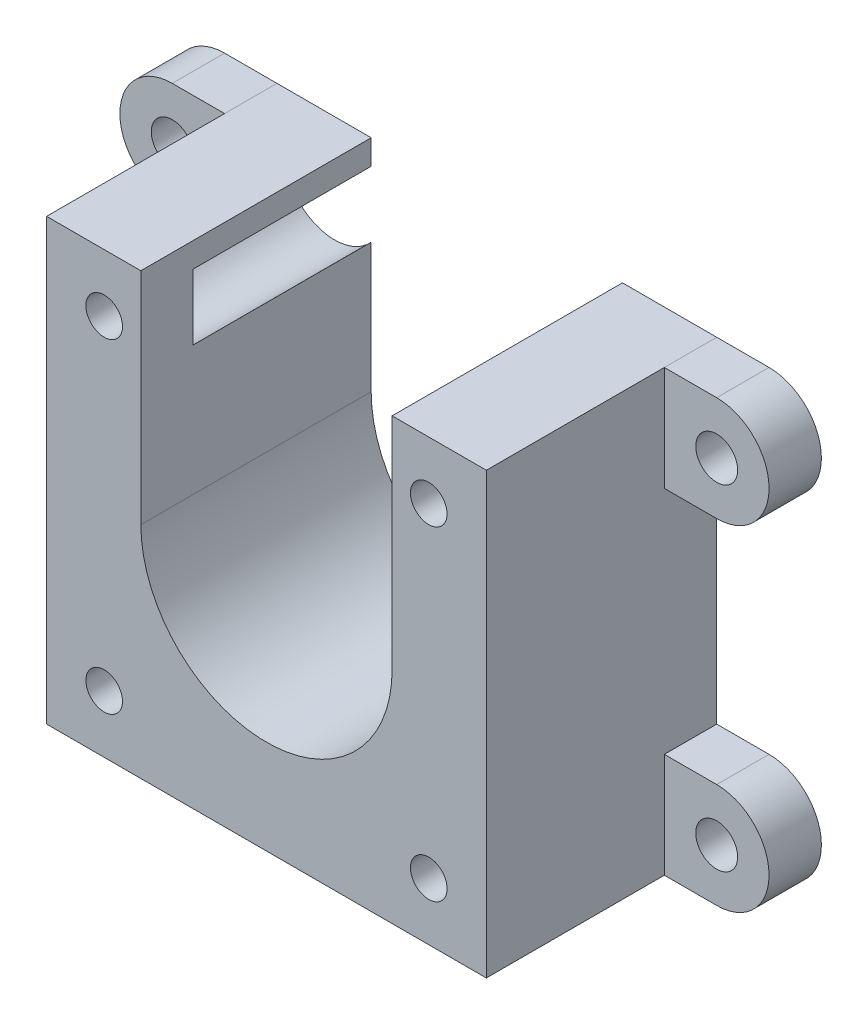
SolidWorks part; units mm, degrees
material "ABS"
ref_plane "Plano frontal" through (0, 0, 0) normal (0, 0, 1) x (1, 0, 0)
ref_plane "Plano superior" through (0, 0, 0) normal (0, 1, 0) x (1, 0, 0)
ref_plane "Plano direito" through (0, 0, 0) normal (1, 0, 0) x (0, 0, -1)
sketch "Esboço1" plane through (0, 0, 0) normal (0, 0, 1) x (1, 0, 0)
  line L0 (-12, 0) -> (-12, 21)
  line L1 (-21, 21) -> (-12, 21)
  line L2 (-21, 21) -> (-21, -21)
  line L3 (-21, -21) -> (21, -21)
  line L4 (21, 21) -> (21, -21)
  line L5 (-21, 21) -> (21, -21) construction
  line L6 (-21, -21) -> (21, 21) construction
  line L7 (12, 0) -> (12, 21)
  line L8 (12, 21) -> (21, 21)
  line L10 (-15.5, 15.5) -> (15.5, 15.5) construction
  line L11 (-15.5, 15.5) -> (-15.5, -15.5) construction
  line L12 (-15.5, -15.5) -> (15.5, -15.5) construction
  line L13 (15.5, 15.5) -> (15.5, -15.5) construction
  line L14 (-15.5, 15.5) -> (15.5, -15.5) construction
  line L15 (-15.5, -15.5) -> (15.5, 15.5) construction
  arc A0 (-12, 0) -> (12, 0) centre (0, 0) ccw
  circle A1 centre (-15.5, 15.5) radius 1.75
  circle A2 centre (15.5, 15.5) radius 1.75
  circle A3 centre (15.5, -15.5) radius 1.75
  circle A4 centre (-15.5, -15.5) radius 1.75
  point P0 (0, 0)
  dimension "D2" = 24
  dimension "D4" = 3.5
  dimension "D1" = 42
  dimension "D3" = 31
extrude "Ressalto-extrusão1" add sketch "Esboço1" along normal blind 22
sketch "Esboço2" plane through (0, 0, 0) normal (0, 0, -1) x (-1, 0, 0)
  circle A0 centre (-15.5, 15.5) radius 4.7
  circle A1 centre (15.5, 15.5) radius 4.7
  circle A2 centre (15.5, -15.5) radius 4.7
  circle A3 centre (-15.5, -15.5) radius 4.7
  dimension "D1" = 9.4
extrude "Corte-extrusão1" cut sketch "Esboço2" against normal offset from surface (17 mm away) 5 up to face at (17.25, -15.5, 22)
sketch "Esboço4" plane through (0, 0, 0) normal (0, 0, -1) x (-1, 0, 0)
  line L0 (-21, 21) -> (-12, 21) construction
  line L1 (-21, -21) -> (-21, 21) construction
  line L2 (0, 23.3931) -> (0, -24.4963) construction
  line L3 (-26, 21) -> (-21, 21)
  line L4 (-26, 11) -> (-21, 11)
  line L5 (-21, 21) -> (-21, 11)
  line L6 (26, -21) -> (21, -21)
  line L7 (26, -11) -> (21, -11)
  line L8 (21, -21) -> (21, -11)
  line L9 (-21, -21) -> (-21, -11)
  line L10 (-26, -11) -> (-21, -11)
  line L11 (-26, -21) -> (-21, -21)
  line L12 (21, 21) -> (21, 11)
  line L13 (26, 11) -> (21, 11)
  line L14 (26, 21) -> (21, 21)
  circle A0 centre (-26, 16) radius 2
  arc A1 (-26, 21) -> (-26, 11) centre (-26, 16) ccw
  circle A2 centre (26, -16) radius 2
  arc A3 (26, -21) -> (26, -11) centre (26, -16) ccw
  arc A4 (-26, -21) -> (-26, -11) centre (-26, -16) cw
  circle A5 centre (-26, -16) radius 2
  arc A6 (26, 21) -> (26, 11) centre (26, 16) cw
  circle A7 centre (26, 16) radius 2
  point P22 (0, 0)
  dimension "D1" = 10
  dimension "D2" = 4
  dimension "D3" = 2
extrude "Ressalto-extrusão2" add sketch "Esboço4" against normal blind 5 separate body
